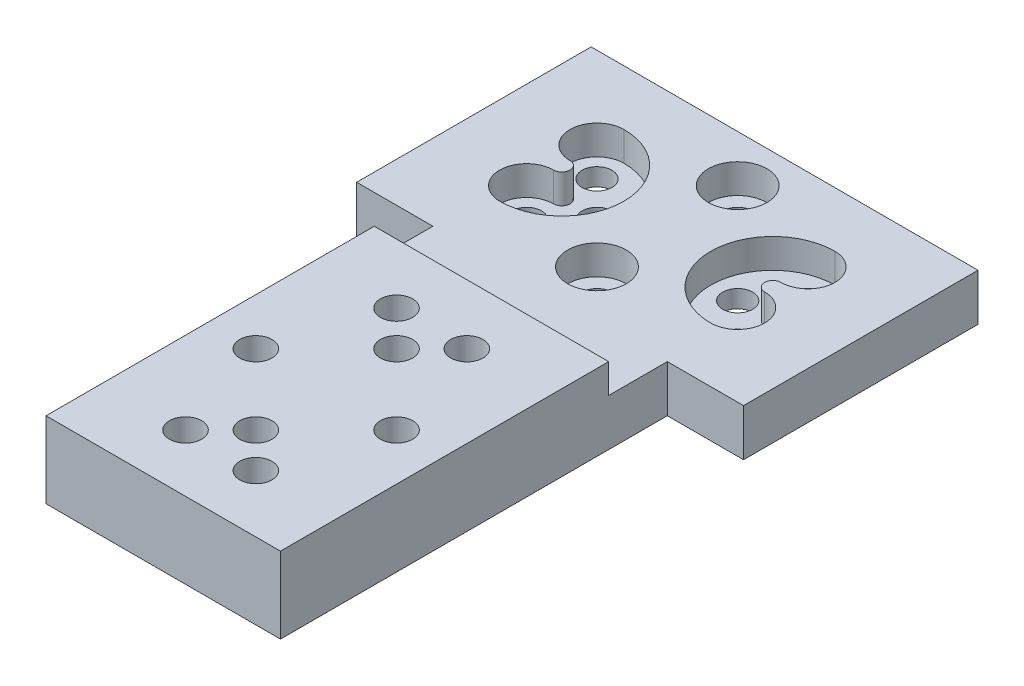
SolidWorks part; units mm, degrees
ref_plane "Front Plane" through (0, 0, 0) normal (0, 0, 1) x (1, 0, 0)
ref_plane "Top Plane" through (0, 0, 0) normal (0, 1, 0) x (1, 0, 0)
ref_plane "Right Plane" through (0, 0, 0) normal (1, 0, 0) x (0, 0, -1)
sketch "Sketch1" plane through (0, 0, 0) normal (0, 1, 0) x (1, 0, 0)
  line L0 (0, 0) -> (20, 0)
  line L1 (20, 0) -> (20, 33)
  line L2 (20, 33) -> (26.5, 33)
  line L3 (26.5, 33) -> (26.5, 53)
  line L4 (26.5, 53) -> (-6.5, 53)
  line L5 (-6.5, 53) -> (-6.5, 33)
  line L6 (-6.5, 33) -> (0, 33)
  line L7 (0, 33) -> (0, 0)
  dimension "D1" = 20
  dimension "D2" = 33
  dimension "D4" = 20
  dimension "D5" = 33
extrude "Boss-Extrude1" add sketch "Sketch1" along normal blind 4
sketch "Sketch2" plane through (0, 4, 0) normal (0, 1, 0) x (1, 0, 0)
  line L0 (20, 0) -> (20, 33) construction
  line L1 (0, 0) -> (20, 0)
  line L2 (0, 0) -> (0, 28)
  line L3 (0, 28) -> (20, 28)
  line L4 (20, 0) -> (20, 28)
  dimension "D1" = 28
extrude "Boss-Extrude2" add sketch "Sketch2" along normal blind 2.5
sketch "Sketch3" plane through (0, 0, 0) normal (0, -1, 0) x (1, 0, 0)
  line L0 (10, 0) -> (10, -53) construction
  line L1 (0, 0) -> (20, 0) construction
  line L2 (26.5, -53) -> (-6.5, -53) construction
  line L4 (0, -28) -> (0, 0) construction
  line L6 (-6.5, -43) -> (26.5, -43) construction
  line L7 (-6.5, -53) -> (-6.5, -33) construction
  line L8 (26.5, -33) -> (26.5, -53) construction
  circle A0 centre (10, -7.9) radius 1.375
  circle A1 centre (7, -4.9) radius 1.375
  circle A2 centre (4, -13.9) radius 1.375
  circle A3 centre (10, -19.9) radius 1.375
  circle A4 centre (7, -22.9) radius 1.375
  circle A5 centre (13, -4.9) radius 1.375
  circle A6 centre (13, -22.9) radius 1.375
  circle A7 centre (16, -13.9) radius 1.375
  circle A8 centre (10, -49) radius 1.275
  circle A9 centre (4, -43) radius 1.275
  circle A10 centre (1, -46) radius 1.275
  circle A11 centre (10, -37) radius 1.275
  circle A12 centre (1, -40) radius 1.275
  circle A13 centre (19, -46) radius 1.275
  circle A14 centre (16, -43) radius 1.275
  circle A15 centre (19, -40) radius 1.275
  point P50 (16.5052, -16.6432)
  dimension "D1" = 2.75
  dimension "D10" = 2.55
  dimension "D2" = 9
  dimension "D3" = 12
  dimension "D4" = 6
  dimension "D5" = 7
  dimension "D6" = 9
  dimension "D7" = 4
  dimension "D8" = 7
  dimension "D11" = 4
  dimension "D12" = 10.5
  dimension "D13" = 7.5
  dimension "D14" = 7
  dimension "D15" = 29.1
extrude "Cut-Extrude1" cut sketch "Sketch3" against normal up to next
sketch "Sketch4" plane through (0, 0, 0) normal (0, -1, 0) x (1, 0, 0)
  line L0 (4, -13.9) -> (16, -13.9) construction
  circle A3 centre (4, -13.9) radius 2.5
  circle A7 centre (16, -13.9) radius 2.5
  arc A10 (13, -22.9) -> (7, -22.9) centre (10, -22.9) ccw construction
  arc A11 (15.5, -22.9) -> (4.5, -22.9) centre (10, -22.9) ccw
  arc A12 (10.5, -22.9) -> (9.5, -22.9) centre (10, -22.9) ccw
  arc A13 (10.5, -22.9) -> (15.5, -22.9) centre (13, -22.9) ccw
  arc A14 (4.5, -22.9) -> (9.5, -22.9) centre (7, -22.9) ccw
  arc A15 (13, -4.9) -> (7, -4.9) centre (10, -4.9) cw construction
  arc A16 (15.5, -4.9) -> (4.5, -4.9) centre (10, -4.9) cw
  arc A17 (10.5, -4.9) -> (9.5, -4.9) centre (10, -4.9) cw
  arc A18 (10.5, -4.9) -> (15.5, -4.9) centre (13, -4.9) cw
  arc A19 (4.5, -4.9) -> (9.5, -4.9) centre (7, -4.9) cw
  point P4 (10, -7.9)
  point P27 (10, -19.9)
  dimension "D1" = 5
  dimension "D2" = 2.5
extrude "Cut-Extrude2" cut sketch "Sketch4" against normal blind 1.5
sketch "Sketch5" plane through (0, 4, 0) normal (0, 1, 0) x (1, 0, 0)
  line L0 (10, 49) -> (10, 37) construction
  circle A0 centre (10, 49) radius 2.5
  circle A7 centre (10, 37) radius 2.5
  arc A8 (19, 46) -> (19, 40) centre (19, 43) ccw construction
  arc A9 (19, 48.3) -> (19, 37.7) centre (19, 43) ccw
  arc A10 (19, 43.7) -> (19, 42.3) centre (19, 43) ccw
  arc A11 (19, 43.7) -> (19, 48.3) centre (19, 46) ccw
  arc A12 (19, 37.7) -> (19, 42.3) centre (19, 40) ccw
  arc A13 (1, 46) -> (1, 40) centre (1, 43) cw construction
  arc A14 (1, 48.3) -> (1, 37.7) centre (1, 43) cw
  arc A15 (1, 43.7) -> (1, 42.3) centre (1, 43) cw
  arc A16 (1, 43.7) -> (1, 48.3) centre (1, 46) cw
  arc A17 (1, 37.7) -> (1, 42.3) centre (1, 40) cw
  point P9 (4, 43)
  point P25 (16, 43)
  dimension "D1" = 5
  dimension "D2" = 2.3
extrude "Cut-Extrude3" cut sketch "Sketch5" against normal blind 2.5
